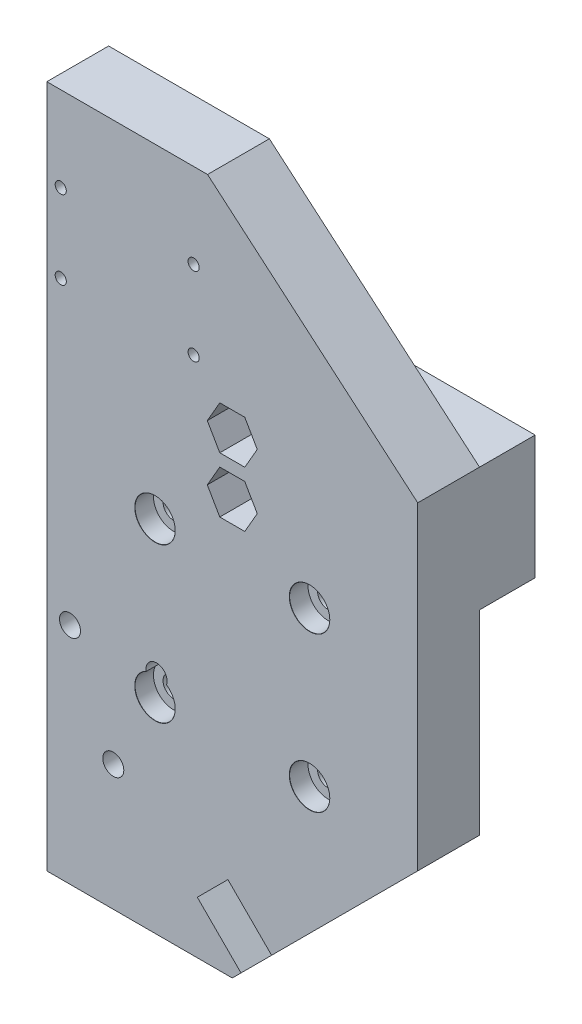
SolidWorks part; units mm, degrees
ref_plane "Front Plane" through (0, 0, 0) normal (0, 0, 1) x (1, 0, 0)
ref_plane "Top Plane" through (0, 0, 0) normal (0, 1, 0) x (1, 0, 0)
ref_plane "Right Plane" through (0, 0, 0) normal (1, 0, 0) x (0, 0, -1)
sketch "Sketch1" plane through (0, 0, 0) normal (0, 0, 1) x (1, 0, 0)
  line L1 (-12.5, 12.5) -> (12.5, 12.5)
  line L2 (-12.5, 12.5) -> (-12.5, -12.5)
  line L3 (-12.5, -12.5) -> (12.5, -12.5)
  line L4 (12.5, 12.5) -> (12.5, -12.5)
  line L5 (-12.5, 12.5) -> (12.5, -12.5) construction
  line L6 (-12.5, -12.5) -> (12.5, 12.5) construction
  line L7 (-30, 36) -> (30, 36)
  line L8 (-30, 36) -> (-30, -36)
  line L9 (-30, -36) -> (30, -36)
  line L10 (30, 36) -> (30, -36)
  line L11 (-30, 36) -> (30, -36) construction
  line L12 (-30, -36) -> (30, 36) construction
  line L13 (-30, -10) -> (30, -10)
  line L14 (-30, -10) -> (-30, 10)
  line L15 (-30, 10) -> (30, 10)
  line L16 (30, -10) -> (30, 10)
  line L17 (-30, -10) -> (30, 10) construction
  line L18 (-30, 10) -> (30, -10) construction
  line L19 (-30, -16) -> (30, -16)
  line L20 (-30, -16) -> (-30, 16)
  line L21 (-30, 16) -> (30, 16)
  line L22 (30, -16) -> (30, 16)
  line L23 (-30, -16) -> (30, 16) construction
  line L24 (-30, 16) -> (30, -16) construction
  point P0 (0, 0)
  point P6 (0, 0)
  point P11 (0, 0)
  point P16 (0, 0)
  dimension "D1" = 25
  dimension "D2" = 25
  dimension "D3" = 60
  dimension "D4" = 20
  dimension "D5" = 20
  dimension "D6" = 32
sketch "Sketch2" plane through (0, 0, 0) normal (0, 0, 1) x (1, 0, 0)
  line L0 (-30, -36) -> (30, -36) construction
  line L1 (-30, 36) -> (-30, -36) construction
  line L2 (-30, 36) -> (30, 36) construction
  line L3 (30, 36) -> (30, -36) construction
  line L4 (-30, -36) -> (30, -36)
  line L5 (-30, 36) -> (-30, -36)
  line L6 (-30, 36) -> (30, 36)
  line L7 (30, 36) -> (30, -36)
extrude "Boss-Extrude1" add sketch "Sketch2" along normal blind 10
sketch "Sketch9" plane through (0, 0, 0) normal (0, 0, -1) x (-1, 0, 0)
  line L0 (30, 36) -> (30, -36) construction
  line L1 (-30, 36) -> (30, 36)
  line L2 (-30, 36) -> (-30, 16)
  line L3 (-30, 16) -> (30, 16)
  line L4 (30, 36) -> (30, 16)
  dimension "D1" = 16
extrude "Boss-Extrude2" add sketch "Sketch9" along normal blind 9
hole_wizard "CBORE for M3 SHCS1" positions "Sketch5" profile "Sketch6" counterbore size "M3" standard "ANSI Metric"
sketch "Sketch5" plane through (0, 0, 10) normal (0, 0, 1) x (1, 0, 0)
  point P0 (-12.5, 12.5)
  point P2 (12.5, 12.5)
  point P4 (12.5, -12.5)
  point P6 (-12.5, -12.5)
sketch "Sketch6" plane through (-12.5, 12.5, 10) normal (1, 0, 0) x (0, -1, 0)
  line L0 (0, 0) -> (0, 11.0215)
  line L1 (0, 11.0215) -> (1.7, 10)
  line L2 (1.7, 10) -> (1.7, 3)
  line L3 (1.7, 3) -> (3.25, 3)
  line L5 (3.25, 3) -> (3.25, 0.025)
  line L6 (3.25, 0.025) -> (3.275, 0)
  line L7 (3.275, 0) -> (0, 0)
  line L8 (-3.25, 0.025) -> (-3.275, 0) construction
  line L10 (0, 11.0215) -> (-1.7, 10) construction
  line L11 (0, -6.35) -> (0, 107.95) construction
  dimension "Hole Dia." = 3.4
  dimension "Hole Depth" = 10
  dimension "C'Bore Dia." = 6.5
  dimension "C'Bore Depth" = 3
  dimension "Near C'Sink Dia." = 6.55
  dimension "Near C'Sink Angle" = 90
  dimension "Drill Angle" = 118
sketch "Sketch7" plane through (0, 0, 10) normal (0, 0, 1) x (1, 0, 0)
  line L1 (-30, 30.5) -> (30, 30.5) construction
  line L2 (-30, 36) -> (-30, -36) construction
  line L3 (30, -36) -> (30, 36) construction
  line L4 (30, 36) -> (-30, 36) construction
  line L5 (-30, 21.5) -> (30, 21.5) construction
  line L6 (-30, 16) -> (30, 16) construction
  line L8 (4.0415, 21.5) -> (2.0207, 25)
  line L9 (2.0207, 25) -> (-2.0207, 25)
  line L10 (-2.0207, 25) -> (-4.0415, 21.5)
  line L11 (-4.0415, 21.5) -> (-2.0207, 18)
  line L12 (-2.0207, 18) -> (2.0207, 18)
  line L13 (2.0207, 18) -> (4.0415, 21.5)
  line L14 (4.0415, 30.5) -> (2.0207, 34)
  line L15 (2.0207, 34) -> (-2.0207, 34)
  line L16 (-2.0207, 34) -> (-4.0415, 30.5)
  line L17 (-4.0415, 30.5) -> (-2.0207, 27)
  line L18 (-2.0207, 27) -> (2.0207, 27)
  line L19 (2.0207, 27) -> (4.0415, 30.5)
  circle A0 centre (0, 21.5) radius 3.5 construction
  circle A1 centre (0, 30.5) radius 3.5 construction
  dimension "D1" = 5.5
  dimension "D2" = 5.5
  dimension "D3" = 7
  dimension "D4" = 7
extrude "Cut-Extrude1" cut sketch "Sketch7" against normal blind 11
sketch "Sketch8" plane through (0, 0, -1) normal (0, 0, 1) x (1, 0, 0)
  line L0 (-4.0415, 21.5) -> (4.0415, 21.5) construction
  line L1 (4.0415, 30.5) -> (-4.0415, 30.5) construction
  circle A0 centre (0, 30.5) radius 2.1
  circle A1 centre (0, 21.5) radius 2.1
  dimension "D1" = 4.2
extrude "Cut-Extrude2" cut sketch "Sketch8" against normal through all
sketch "Sketch10" plane through (0, 0, 10) normal (0, 0, 1) x (1, 0, 0)
  line L0 (-30, -36) -> (30, -36) construction
  line L1 (-25, 31) -> (25, 31)
  line L2 (-25, 31) -> (-25, -31)
  line L3 (-25, -31) -> (25, -31)
  line L4 (25, 31) -> (25, -31)
  line L5 (-25, 31) -> (25, -31) construction
  line L6 (-25, -31) -> (25, 31) construction
  line L7 (30, -36) -> (30, 36) construction
  point P0 (0, 0)
  dimension "D1" = 5
  dimension "D2" = 5
sketch "Sketch14" plane through (0, 0, 10) normal (0, 0, 1) x (1, 0, 0)
  line L0 (30, -36) -> (30, 36) construction
  line L1 (-30, -36) -> (30, -36)
  line L2 (-30, -36) -> (-30, -45.57)
  line L3 (-30, -45.57) -> (30, -45.57)
  line L4 (30, -36) -> (30, -45.57)
  dimension "D1" = 9.57
extrude "Boss-Extrude3" add sketch "Sketch14" against normal up to surface (10 mm away) up to face at (-10.8, 12.5, 0)
sketch "Sketch15" plane through (0, 0, 0) normal (0, 0, -1) x (-1, 0, 0)
  circle A0 centre (26.25, -9.25) radius 1.25 construction
  circle A1 centre (12.25, -9.25) radius 1.25 construction
  circle A2 centre (19.25, -25.25) radius 1.25 construction
  circle A3 centre (26.25, -9.25) radius 1.25
  circle A4 centre (12.25, -9.25) radius 1.25
  circle A5 centre (19.25, -25.25) radius 1.25
hole_wizard "CBORE for M3 SHCS2" positions "Sketch16" profile "Sketch17" counterbore size "M3" standard "ANSI Metric" end condition through all
sketch "Sketch16" plane through (0, 0, 0) normal (0, 0, -1) x (-1, 0, 0)
  point P0 (19.25, -25.25)
  point P3 (12.25, -9.25)
  point P6 (26.25, -9.25)
sketch "Sketch17" plane through (-19.25, -25.25, 0) normal (1, 0, 0) x (0, 1, 0)
  line L0 (0, 0) -> (0, 10)
  line L1 (0, 10) -> (1.7, 10)
  line L3 (1.7, 10) -> (1.7, 3)
  line L4 (1.7, 3) -> (3.25, 3)
  line L5 (3.25, 3) -> (3.25, 0)
  line L7 (3.25, 0) -> (0, 0)
  line L11 (0, -6.35) -> (0, 107.95) construction
  dimension "Thru Hole Dia." = 3.4
  dimension "Thru Hole Depth" = 10
  dimension "C'Bore Dia." = 6.5
  dimension "C'Bore Depth" = 3
sketch "Sketch18" plane through (0, 0, 10) normal (0, 0, 1) x (1, 0, 0)
  line L0 (0, -45.57) -> (30, -15.57)
  line L1 (-30, -45.57) -> (30, -45.57) construction
  line L2 (30, -45.57) -> (30, 36) construction
  line L3 (30, -15.57) -> (30, -45.57)
  line L4 (30, -45.57) -> (0, -45.57)
  dimension "D1" = 45
  dimension "D2" = 30
extrude "Cut-Extrude3" cut sketch "Sketch18" against normal through all
sketch "Sketch19" plane through (0, 0, 10) normal (0, 0, 1) x (1, 0, 0)
  line L0 (-30, 36) -> (-30, 65)
  line L1 (-30, 65) -> (-4, 65)
  line L2 (-4, 65) -> (30, 36)
  line L3 (30, 36) -> (-30, 36)
  dimension "D1" = 26
  dimension "D2" = 29
extrude "Boss-Extrude4" add sketch "Sketch19" against normal blind 10
sketch "Sketch20" plane through (0, 0, 10) normal (0, 0, 1) x (1, 0, 0)
  line L0 (-17, 51.284) -> (-17, 65) construction
  line L1 (-27.75, 51.284) -> (-6.25, 51.284) construction
  line L2 (-27.75, 51.284) -> (-27.75, 38.584) construction
  line L3 (-27.75, 38.584) -> (-6.25, 38.584) construction
  line L4 (-6.25, 51.284) -> (-6.25, 38.584) construction
  line L5 (-4, 65) -> (-30, 65) construction
  circle A0 centre (-27.75, 51.284) radius 0.9
  circle A1 centre (-27.75, 38.584) radius 0.9
  circle A2 centre (-6.25, 38.584) radius 0.9
  circle A3 centre (-6.25, 51.284) radius 0.9
  dimension "D1" = 1.8
  dimension "D2" = 12.7
  dimension "D3" = 21.5
  dimension "D4" = 13.716
extrude "Cut-Extrude4" cut sketch "Sketch20" against normal blind 10
sketch "Sketch21" plane through (22.785, -22.785, 0) normal (0.7071, -0.7071, 0) x (0, 0, -1)
  line L0 (-10, 10.2036) -> (-10, -32.2229) construction
  line L1 (-10, -30.2229) -> (-5, -30.2229)
  line L2 (-10, -30.2229) -> (-10, -23.2229)
  line L3 (-10, -23.2229) -> (-5, -23.2229)
  line L4 (-5, -30.2229) -> (-5, -23.2229)
  line L5 (-10, -32.2229) -> (0, -32.2229) construction
  circle A0 centre (-7.5, -18.268) radius 1.85 construction
  circle A1 centre (-7.5, -18.268) radius 1.85 construction
  dimension "D1" = 2
  dimension "D2" = 7
  dimension "D3" = 5
extrude "Cut-Extrude5" cut sketch "Sketch21" against normal blind 10
